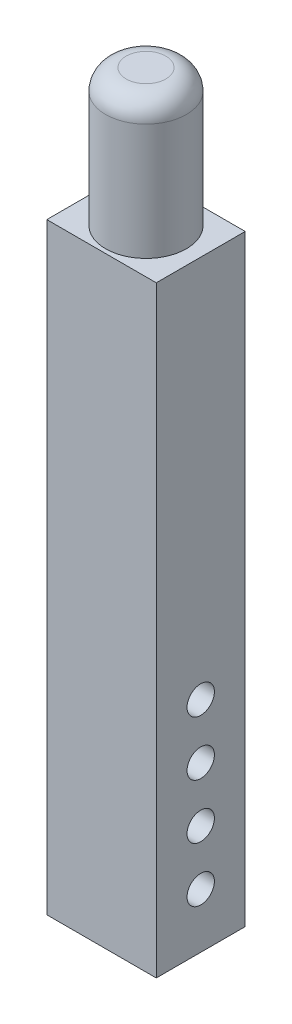
SolidWorks part; units mm, degrees
ref_plane "Front Plane" through (0, 0, 0) normal (0, 0, 1) x (1, 0, 0)
ref_plane "Top Plane" through (0, 0, 0) normal (0, 1, 0) x (1, 0, 0)
ref_plane "Right Plane" through (0, 0, 0) normal (1, 0, 0) x (0, 0, -1)
sketch "Sketch1" plane through (0, 0, 0) normal (0, 1, 0) x (1, 0, 0)
  line L0 (0, -55) -> (0, 55) construction
  line L1 (-5.08, 4.1275) -> (5.08, 4.1275)
  line L2 (-5.08, 4.1275) -> (-5.08, -4.1275)
  line L3 (-5.08, -4.1275) -> (5.08, -4.1275)
  line L4 (5.08, 4.1275) -> (5.08, -4.1275)
  line L5 (-55, 0) -> (55, 0) construction
  point P4 (0, 4.1275)
  point P7 (-5.08, 0)
  dimension "D1" = 8.255
  dimension "D2" = 10.16
extrude "Boss-Extrude1" add sketch "Sketch1" along normal blind 55.88
sketch "Sketch2" plane through (0, 55.88, 0) normal (0, 1, 0) x (1, 0, 0)
  circle A0 centre (0, 0) radius 3.7465
  dimension "D1" = 7.493
extrude "Boss-Extrude2" add sketch "Sketch2" along normal blind 12.7
sketch "Sketch3" plane through (5.08, 0, 0) normal (1, 0, 0) x (0, 0, -1)
  line L0 (-4.1275, 0) -> (4.1275, 0) construction
  circle A0 centre (0, 5.08) radius 1.27
  dimension "D1" = 2.54
  dimension "D2" = 5.08
extrude "Cut-Extrude2" cut sketch "Sketch3" against normal through all
pattern_linear "LPattern1" count 4 spacing 5.08 along (0, 1, 0) of "Cut-Extrude2"
fillet "Fillet1" radius 1.905 1 edges at (0, 68.58, 3.7465)
